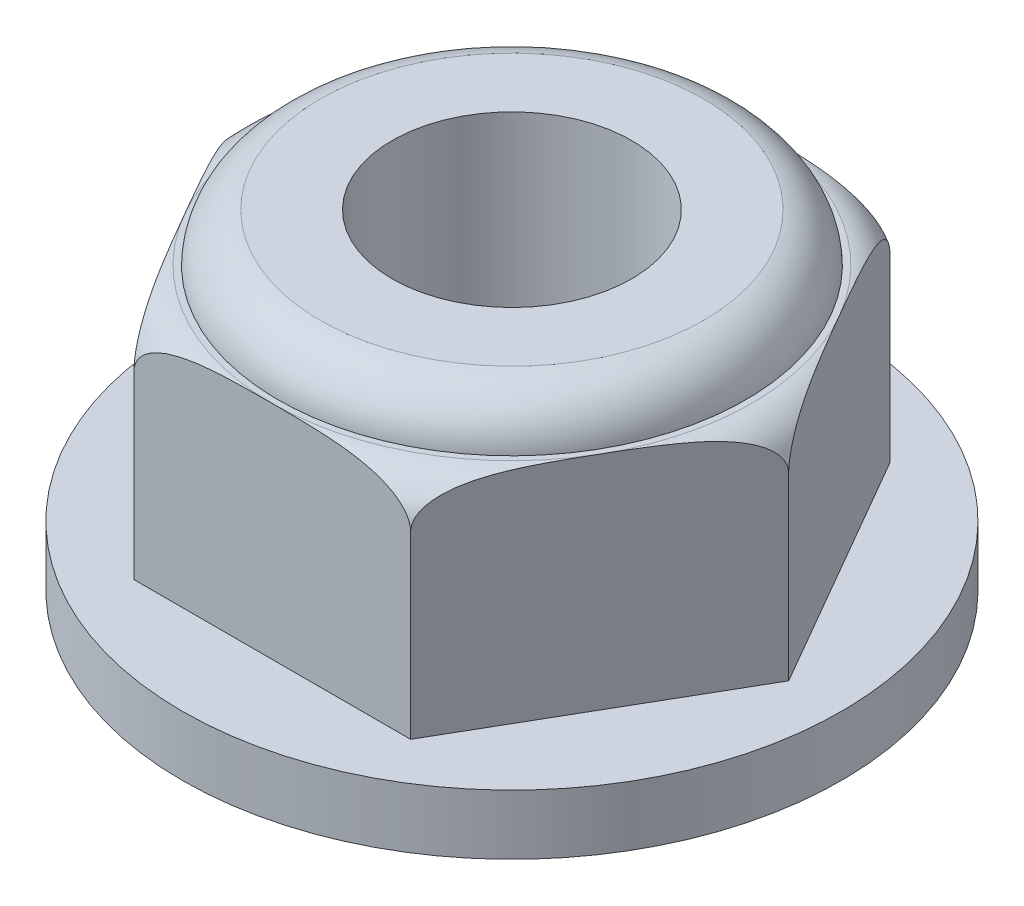
SolidWorks part; units mm, degrees
ref_plane "前视基准面" through (0, 0, 0) normal (0, 0, 1) x (1, 0, 0)
ref_plane "上视基准面" through (0, 0, 0) normal (0, 1, 0) x (1, 0, 0)
ref_plane "右视基准面" through (0, 0, 0) normal (1, 0, 0) x (0, 0, -1)
sketch "草图1" plane through (0, 0, 0) normal (0, 1, 0) x (1, 0, 0)
  circle A0 centre (0, 0) radius 5.5
  circle A1 centre (0, 0) radius 2
extrude "凸台-拉伸1" add sketch "草图1" along normal blind 1
sketch "草图2" plane through (0, 1, 0) normal (0, 1, 0) x (1, 0, 0)
  line L1 (4.6188, 0) -> (2.3094, 4)
  line L2 (2.3094, 4) -> (-2.3094, 4)
  line L3 (-2.3094, 4) -> (-4.6188, 0)
  line L4 (-4.6188, 0) -> (-2.3094, -4)
  line L5 (-2.3094, -4) -> (2.3094, -4)
  line L6 (2.3094, -4) -> (4.6188, 0)
  circle A0 centre (0, 0) radius 4 construction
  circle A1 centre (0, 0) radius 2
extrude "凸台-拉伸2" add sketch "草图2" along normal blind 4.5
sketch "草图3" plane through (0, 0, 0) normal (0, 0, 1) x (1, 0, 0)
  line L6 (0, 5.5) -> (0, 4.7)
  line L9 (-4.6188, 5.5) -> (-4.6188, 1) construction
  line L11 (-4.6188, 5.5) -> (-4.6188, 4)
  line L12 (-3.2, 5.5) -> (-4.6188, 5.5)
  line L13 (-2.3094, 5.5) -> (2.3094, 5.5) construction
  line L15 (-4, 4.7) -> (-3.9, 4.7)
  arc A1 (-4.6188, 4) -> (-4, 4.7) centre (-3.9135, 4) cw
  arc A2 (-3.2, 5.5) -> (-3.9, 4.7) centre (-3.0337, 4.6482) ccw
revolve "切除-旋转1" cut sketch "草图3" angle 360 about L6
